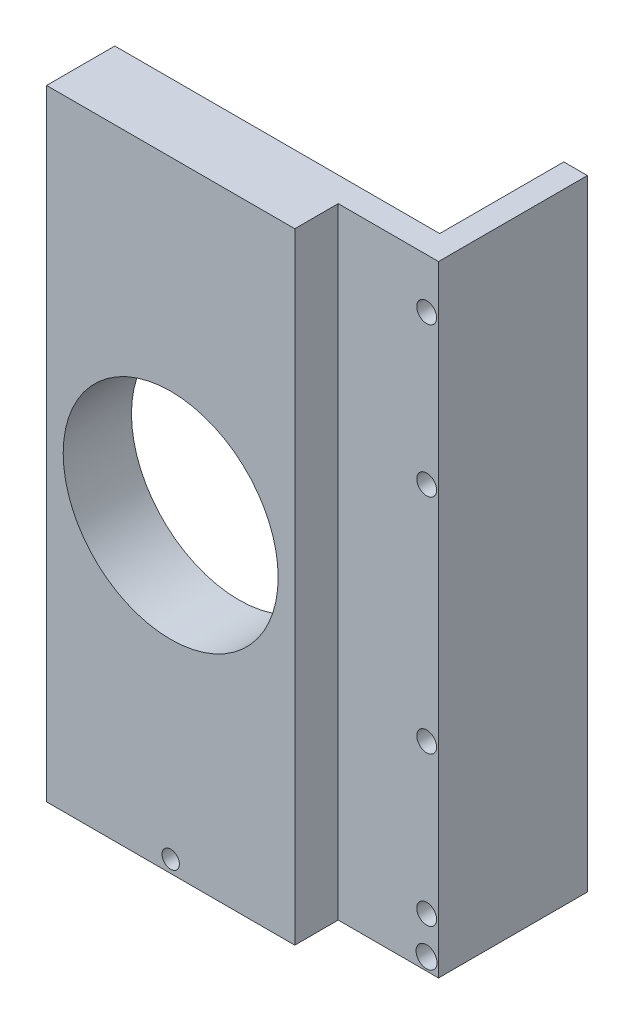
SolidWorks part; units mm, degrees
ref_plane "Front Plane" through (0, 0, 0) normal (0, 0, 1) x (1, 0, 0)
ref_plane "Top Plane" through (0, 0, 0) normal (0, 1, 0) x (1, 0, 0)
ref_plane "Right Plane" through (0, 0, 0) normal (1, 0, 0) x (0, 0, -1)
sketch "Sketch1" plane through (0, 0, 0) normal (0, 0, 1) x (1, 0, 0)
  line L0 (19.05, 31.75) -> (16.632, 31.75)
  line L1 (-19.05, 31.75) -> (19.05, 31.75)
  line L2 (-19.05, 31.75) -> (-19.05, -31.75)
  line L3 (-19.05, -31.75) -> (19.05, -31.75)
  line L4 (19.05, 31.75) -> (19.05, -31.75)
  line L5 (-19.05, 31.75) -> (19.05, -31.75) construction
  line L6 (-19.05, -31.75) -> (19.05, 31.75) construction
  line L7 (19.05, 31.75) -> (16.632, 31.75)
  line L8 (19.05, 31.75) -> (19.05, -31.75)
  line L9 (19.05, -31.75) -> (16.632, -31.75)
  line L10 (16.632, 31.75) -> (16.632, -31.75)
  line L11 (-19.05, 31.75) -> (-16.6124, 31.75)
  line L12 (-19.05, 31.75) -> (-19.05, -31.75)
  line L13 (-19.05, -31.75) -> (-16.6124, -31.75)
  line L14 (-16.6124, 31.75) -> (-16.6124, -31.75)
  line L15 (17.841, 31.75) -> (17.841, 26.6578)
  line L16 (17.841, 26.6578) -> (17.841, 11.3858)
  line L17 (19.05, 0) -> (17.841, 0)
  line L18 (0, 31.75) -> (0, 21.4812) construction
  circle A0 centre (17.841, 26.6578) radius 1.016
  circle A1 centre (17.841, 11.3858) radius 1.016
  circle A2 centre (17.841, -26.6578) radius 1.016
  circle A3 centre (17.841, -11.3858) radius 1.016
  circle A4 centre (-17.841, -26.6578) radius 1.016
  circle A5 centre (-17.841, -11.3858) radius 1.016
  circle A6 centre (-17.841, 11.3858) radius 1.016
  circle A7 centre (-17.841, 26.6578) radius 1.016
  point P0 (0, 0)
  dimension "D1" = 63.5
  dimension "D2" = 38.1
extrude "Boss-Extrude1" add sketch "Sketch1" against normal blind 15.24
sketch "Sketch2" plane through (0, 0, 0) normal (0, 0, 1) x (1, 0, 0)
  line L0 (-16.6124, 31.75) -> (-16.6124, -31.75) construction
  line L1 (16.632, 31.75) -> (-16.6124, 31.75)
  line L2 (16.632, 31.75) -> (16.632, -31.75)
  line L3 (16.632, -31.75) -> (-16.6124, -31.75)
  line L4 (-16.6124, 31.75) -> (-16.6124, -31.75)
extrude "Boss-Extrude2" add sketch "Sketch2" against normal blind 2.54
sketch "Sketch3" plane through (0, -31.75, 0) normal (0, -1, 0) x (1, 0, 0)
  line L1 (-19.05, 0) -> (19.05, 0)
  line L2 (-19.05, 0) -> (-19.05, -15.24)
  line L3 (-19.05, -15.24) -> (19.05, -15.24)
  line L4 (19.05, 0) -> (19.05, -15.24)
extrude "Boss-Extrude3" add sketch "Sketch3" against normal blind 2.54
sketch "Sketch4" plane through (0, 0, 0) normal (0, 0, 1) x (1, 0, 0)
  circle A0 centre (-17.841, -26.6578) radius 1.016
extrude "Cut-Extrude1" cut sketch "Sketch4" against normal through all
sketch "Sketch5" plane through (0, 0, 0) normal (0, 0, 1) x (1, 0, 0)
  line L0 (-19.05, -30.48) -> (-17.8278, -30.48) construction
  line L1 (-19.05, -29.21) -> (-19.05, -31.75) construction
  line L2 (0, -31.8452) -> (0, -30.6248) construction
  circle A0 centre (-17.8278, -30.48) radius 1.0717
  circle A1 centre (17.8278, -30.48) radius 1.0717
extrude "Cut-Extrude2" cut sketch "Sketch5" against normal through all contours A1 | A0
sketch "Sketch6" plane through (0, 0, 0) normal (0, 0, 1) x (1, 0, 0)
  line L0 (-16.6124, 0) -> (-3.9124, 0) construction
  line L1 (-16.6124, 31.75) -> (-16.6124, -29.21) construction
  circle A0 centre (-3.9124, 0) radius 11
  dimension "D2" = 22
  dimension "D1" = 12.7
extrude "Cut-Extrude4" cut sketch "Sketch6" against normal through all contours A0
sketch "Sketch7" plane through (0, 0, 0) normal (0, 0, 1) x (1, 0, 0)
  line L0 (-19.05, -31.75) -> (19.05, -31.75) construction
  line L1 (-16.6124, 31.75) -> (8.7876, 31.75)
  line L2 (-16.6124, 31.75) -> (-16.6124, -31.75)
  line L3 (-16.6124, -31.75) -> (8.7876, -31.75)
  line L4 (8.7876, 31.75) -> (8.7876, -31.75)
  circle A0 centre (-3.9124, 0) radius 11
  dimension "D1" = 25.4
extrude "Boss-Extrude4" add sketch "Sketch7" along normal blind 4.445
sketch "Sketch8" plane through (0, 0, -15.24) normal (0, 0, -1) x (-1, 0, 0)
  line L1 (-16.632, -29.21) -> (19.05, -29.21)
  line L2 (-16.632, -29.21) -> (-16.632, -31.75)
  line L3 (-16.632, -31.75) -> (19.05, -31.75)
  line L4 (19.05, -29.21) -> (19.05, -31.75)
extrude "Cut-Extrude5" cut sketch "Sketch8" against normal blind 12.7
sketch "Sketch9" plane through (0, 0, 4.445) normal (0, 0, 1) x (1, 0, 0)
  line L0 (-16.6124, -29.21) -> (8.7876, -29.21) construction
  line L1 (8.7876, -31.75) -> (8.7876, 31.75) construction
  line L2 (8.7876, -29.21) -> (8.7876, -31.75) construction
  line L3 (-16.6124, -31.75) -> (8.7876, -31.75) construction
  line L4 (8.7876, -29.21) -> (-6.4524, -29.21)
  line L5 (8.7876, -29.21) -> (8.7876, -31.75)
  line L6 (8.7876, -31.75) -> (-6.4524, -31.75)
  line L7 (-6.4524, -29.21) -> (-6.4524, -31.75)
  circle A0 centre (-3.9124, -30.48) radius 0.889
  dimension "D1" = 1.778
  dimension "D2" = 15.24
extrude "Cut-Extrude6" cut sketch "Sketch9" against normal blind 12.7 contours A0
sketch "Sketch10" plane through (0, 0, 4.445) normal (0, 0, 1) x (1, 0, 0)
  line L1 (-6.4524, -31.75) -> (8.7876, -31.75)
  line L2 (-6.4524, -31.75) -> (-6.4524, -29.21)
  line L3 (-6.4524, -29.21) -> (8.7876, -29.21)
  line L4 (8.7876, -31.75) -> (8.7876, -29.21)
